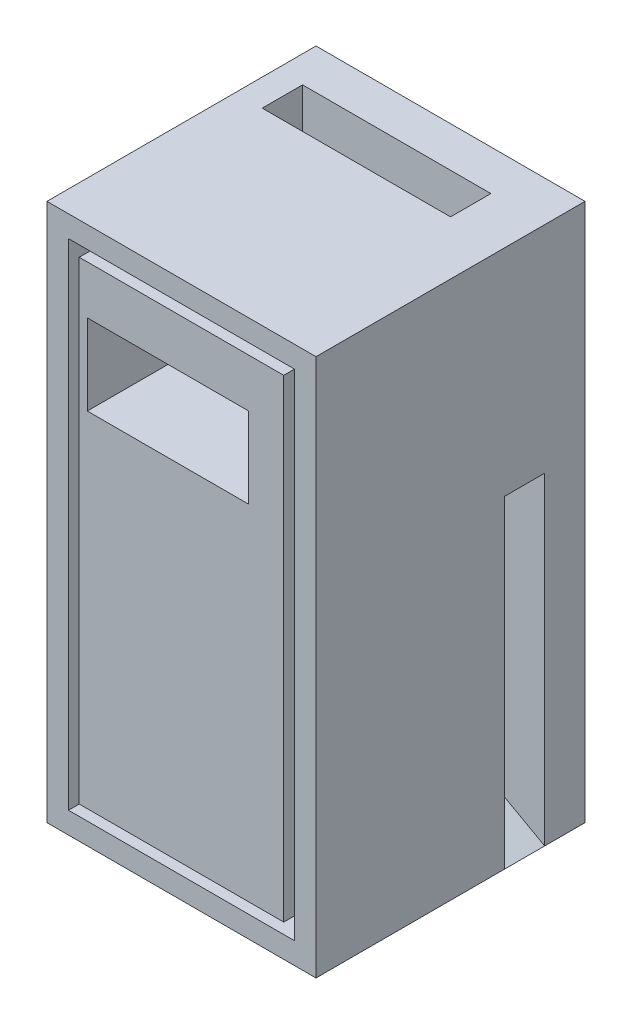
SolidWorks part; units mm, degrees
ref_plane "Front Plane" through (0, 0, 0) normal (0, 0, 1) x (1, 0, 0)
ref_plane "Top Plane" through (0, 0, 0) normal (0, 1, 0) x (1, 0, 0)
ref_plane "Right Plane" through (0, 0, 0) normal (1, 0, 0) x (0, 0, -1)
sketch "Sketch1" plane through (0, 0, 0) normal (0, 0, 1) x (1, 0, 0)
  line L0 (0, 0) -> (45, 0)
  line L1 (0, 0) -> (-5, 0)
  line L3 (0, 25) -> (-5, 25)
  line L4 (-5, 0) -> (-5, 25)
  line L5 (45, 0) -> (0, 25)
  point P5 (0, 0)
  point P7 (0, 0)
  point P8 (0, 0)
  point P9 (0, 0)
  dimension "D1" = 5
  dimension "D2" = 25
  dimension "D3" = 50
extrude "Boss-Extrude1" add sketch "Sketch1" along normal mid plane 50
sketch "Sketch2" plane through (0, 0, 0) normal (0, 1, 0) x (1, 0, 0)
  line L1 (45, -25) -> (-5, -25)
  line L2 (45, -25) -> (45, 10)
  line L3 (45, 10) -> (-5, 10)
  line L4 (-5, -25) -> (-5, 10)
  line L5 (45, -25) -> (45, 25) construction
  line L6 (-5, 25) -> (45, 25)
  line L7 (-5, 25) -> (-5, 17.5)
  line L8 (-5, 17.5) -> (45, 17.5)
  line L9 (45, 25) -> (45, 17.5)
  line L10 (-5, -25) -> (-5, 25) construction
  dimension "D1" = 35
  dimension "D2" = 7.5
extrude "Boss-Extrude2" add sketch "Sketch2" along normal blind 100
sketch "Sketch3" plane through (0, 25, 0) normal (0, 1, 0) x (1, 0, 0)
  line L1 (-5, 17.5) -> (0, 17.5)
  line L2 (-5, 17.5) -> (-5, 10)
  line L3 (-5, 10) -> (0, 10)
  line L4 (0, 17.5) -> (0, 10)
extrude "Boss-Extrude3" add sketch "Sketch3" along normal up to surface (75 mm away) up to face at (20, 100, -21.25)
sketch "Sketch4" plane through (0, 0, -17.5) normal (0, 0, 1) x (1, 0, 0)
  line L0 (-5, 0) -> (45, 0) construction
  line L1 (45, 100) -> (35, 100)
  line L2 (45, 100) -> (45, 60)
  line L3 (45, 60) -> (35, 60)
  line L4 (35, 100) -> (35, 60)
  dimension "D1" = 10
  dimension "D2" = 40
extrude "Boss-Extrude4" add sketch "Sketch4" along normal up to surface (7.5 mm away) up to face at (22.5, 56.25, -10)
sketch "Sketch5" plane through (0, 0, 25) normal (0, 0, 1) x (1, 0, 0)
  line L0 (35, 100) -> (0, 100) construction
  line L1 (2.5, 70) -> (32.5, 70)
  line L2 (2.5, 70) -> (2.5, 85)
  line L3 (2.5, 85) -> (32.5, 85)
  line L4 (32.5, 70) -> (32.5, 85)
  line L6 (-5, 100) -> (45, 100) construction
  point P6 (17.5, 100)
  point P7 (17.5, 85)
  dimension "D1" = 15
  dimension "D2" = 30
  dimension "D3" = 15
extrude "Cut-Extrude1" cut sketch "Sketch5" against normal up to next
sketch "Sketch7" plane through (0, 0, 25) normal (0, 0, 1) x (1, 0, 0)
  line L8 (1, 6) -> (39, 6)
  line L9 (39, 6) -> (39, 94)
  line L10 (39, 94) -> (1, 94)
  line L11 (1, 94) -> (1, 6)
  line L12 (1, 6) -> (39, 6)
  line L13 (39, 6) -> (39, 94)
  line L14 (39, 94) -> (1, 94)
  line L15 (1, 94) -> (1, 6)
  line L16 (-1, 4) -> (41, 4)
  line L17 (41, 4) -> (41, 96)
  line L18 (41, 96) -> (-1, 96)
  line L19 (-1, 96) -> (-1, 4)
  line L24 (-1, 4) -> (41, 4)
  line L25 (41, 4) -> (41, 96)
  line L26 (41, 96) -> (-1, 96)
  line L27 (-1, 96) -> (-1, 4)
  dimension "D1" = 6
  dimension "D2" = 4
extrude "Cut-Extrude2" cut sketch "Sketch7" against normal blind 15
